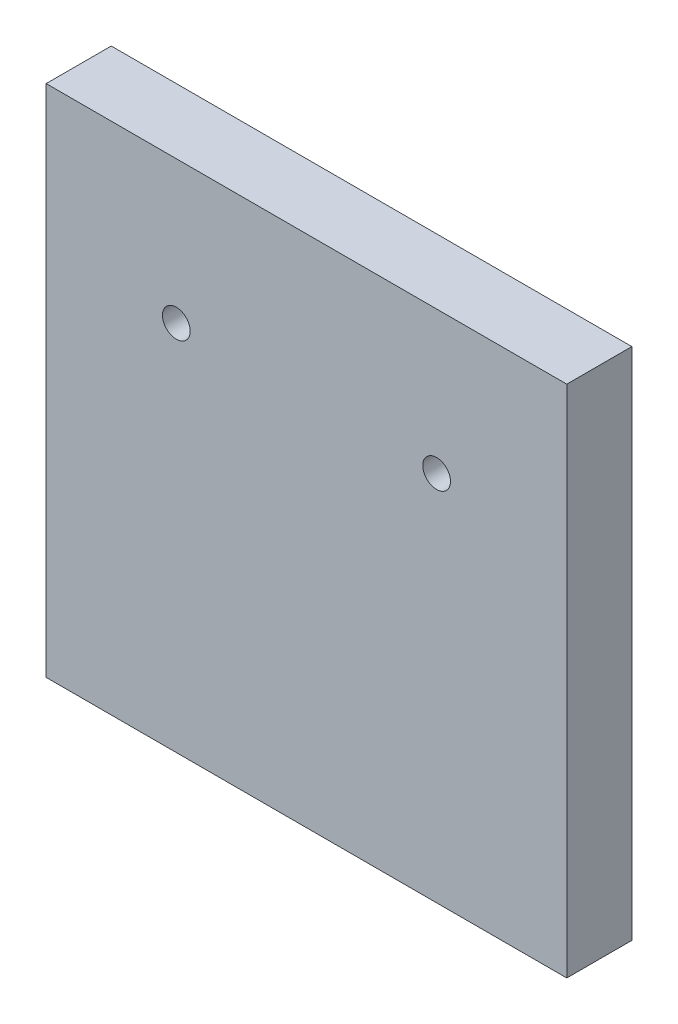
SolidWorks part; units mm, degrees
ref_plane "Front Plane" through (0, 0, 0) normal (0, 0, 1) x (1, 0, 0)
ref_plane "Top Plane" through (0, 0, 0) normal (0, 1, 0) x (1, 0, 0)
ref_plane "Right Plane" through (0, 0, 0) normal (1, 0, 0) x (0, 0, -1)
sketch "Sketch1" plane through (0, 0, 0) normal (0, 0, 1) x (1, 0, 0)
  line L1 (25.4, 13.9) -> (-25.4, 13.9)
  line L2 (25.4, 13.9) -> (25.4, -36.2842)
  line L3 (25.4, -36.2842) -> (-25.4, -36.2842)
  line L4 (-25.4, 13.9) -> (-25.4, -36.2842)
  line L5 (-12.7, 0) -> (12.7, 0) construction
  line L6 (0, -36.2842) -> (0, 13.9) construction
  point P12 (0, 0)
  dimension "D1" = 50.8
  dimension "D2" = 25.4
extrude "Boss-Extrude1" add sketch "Sketch1" along normal blind 6.35 contours L4 L3 L2 L1
hole_wizard "#6-32 Tapped Hole1" positions "Sketch3" profile "Sketch4" tap size "#6-32" standard "ANSI Inch" end condition through all
sketch "Sketch3" plane through (0, 0, 0) normal (0, 0, -1) x (-1, 0, 0)
  line L0 (-12.7, 0) -> (12.7, 0) construction
  point P0 (-12.7, 0)
  point P3 (12.7, 0)
  dimension "D1" = 25.4
sketch "Sketch4" plane through (12.7, 0, 0) normal (1, 0, 0) x (0, 1, 0)
  line L0 (0, 0) -> (0, 6.35)
  line L1 (0, 6.35) -> (1.3525, 6.35)
  line L2 (1.3525, 6.35) -> (1.3525, 0)
  line L5 (1.3525, 0) -> (0, 0)
  line L11 (0, -6.35) -> (0, 107.95) construction
  dimension "Thru Tap Drill Dia." = 2.7051
  dimension "Thru Tap Drill Depth" = 6.35
cosmetic thread "Hole Thread1" parameters "D2"=3.5052
cosmetic thread "Hole Thread2" parameters "D2"=3.5052
